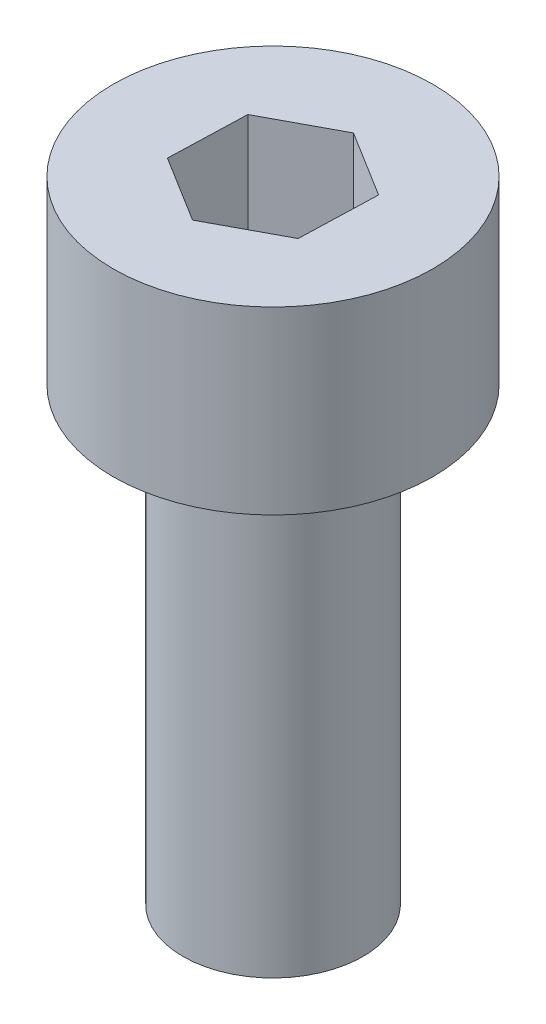
SolidWorks part; units mm, degrees
ref_plane "Front Plane" through (0, 0, 0) normal (0, 0, 1) x (1, 0, 0)
ref_plane "Top Plane" through (0, 0, 0) normal (0, 1, 0) x (1, 0, 0)
ref_plane "Right Plane" through (0, 0, 0) normal (1, 0, 0) x (0, 0, -1)
sketch "Sketch1" plane through (0, 0, 0) normal (0, 1, 0) x (1, 0, 0)
  circle A0 centre (0, 0) radius 3.55
  dimension "D1" = 7.1
extrude "Boss-Extrude1" add sketch "Sketch1" along normal blind 4
sketch "Sketch2" plane through (0, 0, 0) normal (0, -1, 0) x (1, 0, 0)
  circle A0 centre (0, 0) radius 2
  dimension "D1" = 4
extrude "Boss-Extrude2" add sketch "Sketch2" along normal blind 10
sketch "Sketch3" plane through (0, 4, 0) normal (0, 1, 0) x (1, 0, 0)
  line L1 (0.0552, 1.7312) -> (-1.4717, 0.9133)
  line L2 (-1.4717, 0.9133) -> (-1.5268, -0.8178)
  line L3 (-1.5268, -0.8178) -> (-0.0552, -1.7312)
  line L4 (-0.0552, -1.7312) -> (1.4717, -0.9133)
  line L5 (1.4717, -0.9133) -> (1.5268, 0.8178)
  line L6 (1.5268, 0.8178) -> (0.0552, 1.7312)
  circle A0 centre (0, 0) radius 1.5 construction
  dimension "D1" = 3
extrude "Cut-Extrude1" cut sketch "Sketch3" against normal blind 3
equation "\"7。1\"=32.2323"
